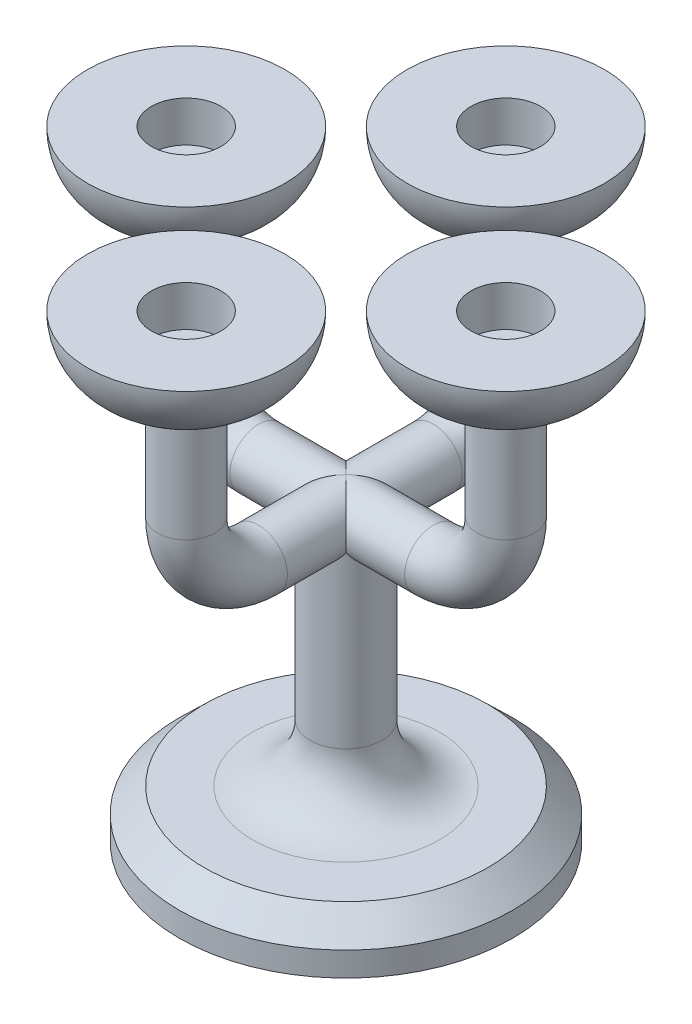
SolidWorks part; units mm, degrees
ref_plane "Front Plane" through (0, 0, 0) normal (0, 0, 1) x (1, 0, 0)
ref_plane "Top Plane" through (0, 0, 0) normal (0, 1, 0) x (1, 0, 0)
ref_plane "Right Plane" through (0, 0, 0) normal (1, 0, 0) x (0, 0, -1)
sketch "Sketch1" plane through (0, 0, 0) normal (0, 0, 1) x (1, 0, 0)
  line L0 (0, 0) -> (0, 50.355)
  line L1 (0, 50.355) -> (6.2588, 50.355)
  line L2 (6.2588, 50.355) -> (6.2588, 8.4399)
  line L3 (6.2588, 8.4399) -> (24.6559, 8.4399)
  line L4 (29.0181, 4.22) -> (29.0181, 0)
  line L5 (29.0181, 0) -> (0, 0)
  line L6 (24.6559, 8.4399) -> (29.0181, 4.22)
revolve "Revolve1" add sketch "Sketch1" angle 360 about L0
fillet "Fillet1" radius 10 1 edges at (0, 8.4399, -6.2588)
sketch "Sketch3" plane through (0, 0, 0) normal (0, 0, 1) x (1, 0, 0)
  line L0 (0, 50.355) -> (15.2059, 50.355)
  line L1 (6.2588, 50.355) -> (-6.2588, 50.355) construction
  line L2 (27.8019, 62.951) -> (27.8019, 82.8043)
  arc A0 (15.2059, 50.355) -> (27.8019, 62.951) centre (15.2059, 62.951) ccw
sweep "Sweep1" add path "Sketch3" circular profile diameter 10 parameters "D3"=10
sketch "Sketch9" plane through (0, 0, 0) normal (0, 0, 1) x (1, 0, 0)
  line L0 (27.8019, 82.8043) -> (33.8581, 82.8043)
  line L2 (32.8019, 82.8043) -> (22.8019, 82.8043) construction
  line L3 (44.9714, 93.9177) -> (33.8581, 93.9177)
  line L4 (33.8581, 93.9177) -> (33.8581, 86.8301)
  line L5 (33.8581, 86.8301) -> (27.8019, 86.8301)
  line L6 (27.8019, 86.8301) -> (27.8019, 82.8043)
  arc A0 (33.8581, 82.8043) -> (44.9714, 93.9177) centre (33.8581, 93.9177) ccw
  point P6 (42.0286, 93.9177)
revolve "Revolve2" add sketch "Sketch9" angle 360 about L6
pattern_circular "CirPattern2" count 4 over 360 about axis through (0, 0, 0) along (0, 1, 0) of "Revolve2", "Sweep1"
